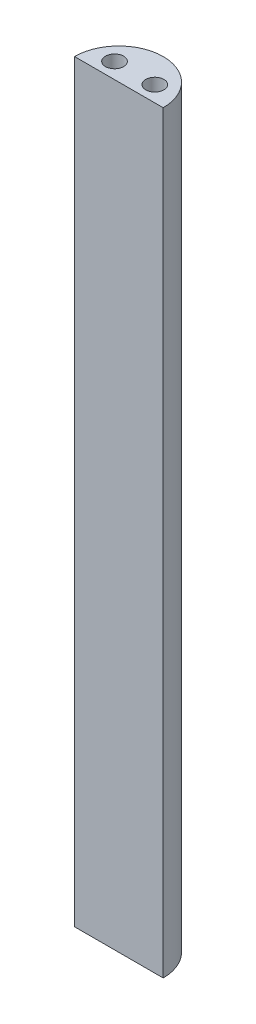
SolidWorks part; units mm, degrees
ref_plane "Front Plane" through (0, 0, 0) normal (0, 0, 1) x (1, 0, 0)
ref_plane "Top Plane" through (0, 0, 0) normal (0, 1, 0) x (1, 0, 0)
ref_plane "Right Plane" through (0, 0, 0) normal (1, 0, 0) x (0, 0, -1)
sketch "Sketch1" plane through (0, 0, 0) normal (0, 1, 0) x (1, 0, 0)
  line L0 (-25.4, 0) -> (25.4, 0)
  arc A0 (25.4, 0) -> (-25.4, 0) centre (0, 0) ccw
  dimension "D1" = 25.4
extrude "Boss-Extrude1" add sketch "Sketch1" along normal blind 431.8
sketch "Sketch2" plane through (0, 431.8, 0) normal (0, 1, 0) x (1, 0, 0)
  line L0 (0, 25.4) -> (0, 9.0574) construction
  line L1 (0, 9.0574) -> (11.545, 9.0574) construction
  line L2 (0, 9.0574) -> (-11.545, 9.0574) construction
  arc A0 (25.4, 0) -> (-25.4, 0) centre (0, 0) ccw construction
  circle A1 centre (-11.545, 9.0574) radius 5.207
  circle A2 centre (11.545, 9.0574) radius 5.207
  dimension "D1" = 10.414
  dimension "D2" = 10.414
extrude "Cut-Extrude1" cut sketch "Sketch2" against normal blind 25.4
